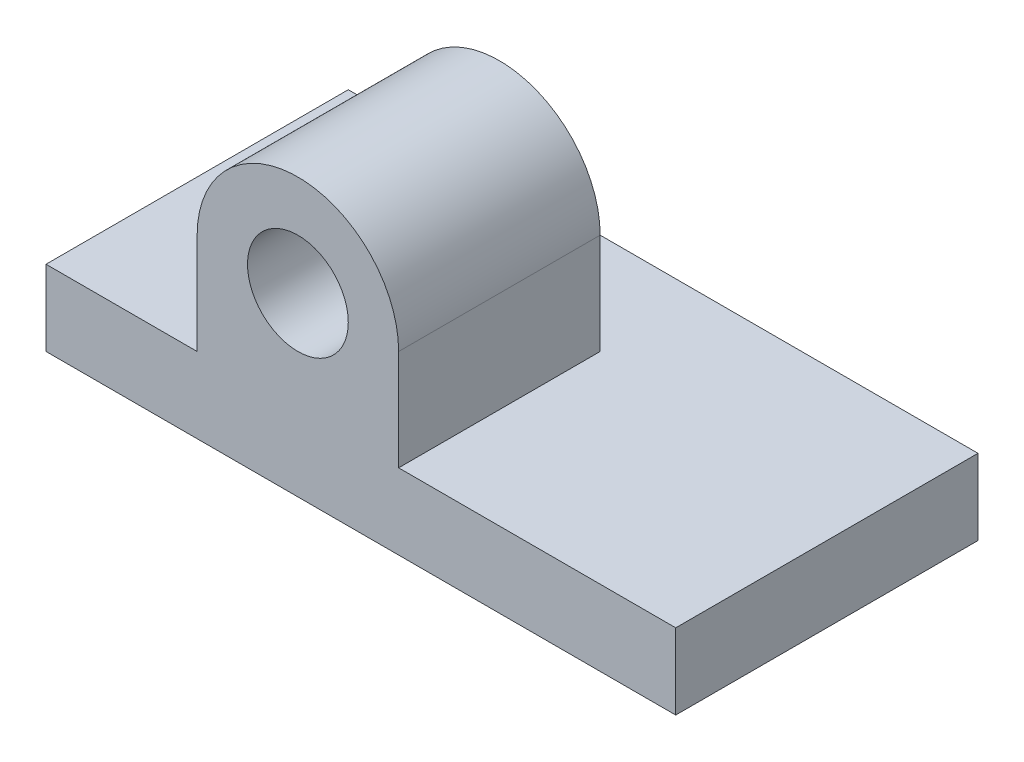
SolidWorks part; units mm, degrees
ref_plane "Płaszczyzna przednia" through (0, 0, 0) normal (0, 0, 1) x (1, 0, 0)
ref_plane "Płaszczyzna górna" through (0, 0, 0) normal (0, 1, 0) x (1, 0, 0)
ref_plane "Płaszczyzna prawa" through (0, 0, 0) normal (1, 0, 0) x (0, 0, -1)
sketch "Szkic2" plane through (0, 0, 0) normal (0, 0, 1) x (1, 0, 0)
  line L0 (0, 0) -> (125, 0)
  line L1 (125, 0) -> (125, 15)
  line L2 (125, 15) -> (70, 15)
  line L3 (70, 15) -> (70, 35)
  line L4 (30, 35) -> (30, 15)
  line L5 (30, 15) -> (0, 15)
  line L6 (0, 15) -> (0, 0)
  arc A0 (70, 35) -> (30, 35) centre (50, 35) ccw
  circle A1 centre (50, 35) radius 10
  point P12 (0, 0)
  dimension "D3" = 20
  dimension "D6" = 20
  dimension "D7" = 15
  dimension "D1" = 15
  dimension "D2" = 125
  dimension "D4" = 50
  dimension "D5" = 35
extrude "Dodanie-wyciągnięcie1" add sketch "Szkic2" against normal blind 60
sketch "Szkic3" plane through (0, 0, -60) normal (0, 0, -1) x (-1, 0, 0)
  line L0 (-70, 15) -> (-30, 15)
  line L7 (0, 0) -> (0, 15)
  line L8 (0, 15) -> (-30, 15)
  line L9 (-30, 15) -> (-30, 35)
  line L10 (-70, 35) -> (-70, 15)
  line L11 (-70, 15) -> (-125, 15)
  line L12 (-125, 15) -> (-125, 0)
  line L13 (-125, 0) -> (0, 0)
  line L14 (0, 0) -> (0, 15)
  line L15 (0, 15) -> (-30, 15)
  line L16 (-30, 15) -> (-30, 35)
  line L17 (-70, 35) -> (-70, 15)
  line L18 (-70, 15) -> (-125, 15)
  line L19 (-125, 15) -> (-125, 0)
  line L20 (-125, 0) -> (0, 0)
  arc A1 (-30, 35) -> (-70, 35) centre (-50, 35) ccw
  arc A2 (-30, 35) -> (-70, 35) centre (-50, 35) ccw
  circle M9 centre (-50, 35) radius 10
  line M12 (-30, 15) -> (-30, 35)
  arc M13 (-30, 35) -> (-70, 35) centre (-50, 35) ccw
  line M14 (-70, 35) -> (-70, 15)
  dimension "D1" = 0
extrude "Wytnij-wyciągnięcie1" cut sketch "Szkic3" against normal blind 20 contours L0 M14 M12 M13 M9
